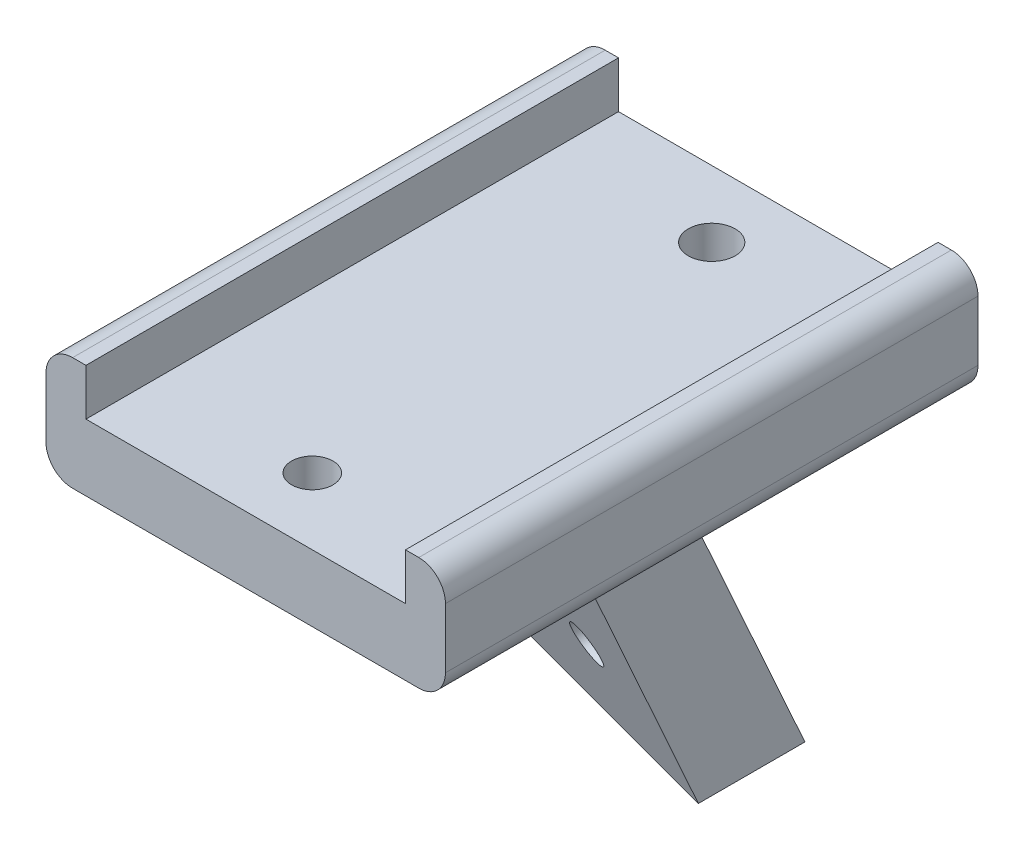
SolidWorks part; units mm, degrees
ref_plane "Front Plane" through (0, 0, 0) normal (0, 0, 1) x (1, 0, 0)
ref_plane "Top Plane" through (0, 0, 0) normal (0, 1, 0) x (1, 0, 0)
ref_plane "Right Plane" through (0, 0, 0) normal (1, 0, 0) x (0, 0, -1)
sketch "Sketch1" plane through (0, 0, 0) normal (0, 1, 0) x (1, 0, 0)
  line L1 (-11, -20) -> (11, -20)
  line L2 (-11, -20) -> (-11, 20)
  line L3 (-11, 20) -> (11, 20)
  line L4 (11, -20) -> (11, 20)
  line L5 (-11, -20) -> (11, 20) construction
  line L6 (-11, 20) -> (11, -20) construction
  circle A0 centre (0, 15) radius 1.7606
  circle A1 centre (0, -15) radius 1.5554
  point P0 (0, 0)
  dimension "D3" = 30
  dimension "D4" = 15
  dimension "D1" = 22
  dimension "D2" = 40
extrude "Boss-Extrude1" add sketch "Sketch1" along normal blind 5
sketch "Sketch2" plane through (0, 0, 0) normal (0, -1, 0) x (1, 0, 0)
  line L0 (-11, 0.1051) -> (11, 6)
  line L1 (-11, -20) -> (-11, 20) construction
  line L2 (11, 20) -> (11, -20) construction
  line L3 (11, 6) -> (11, -2)
  line L4 (11, -2) -> (-11, -7.8949)
  line L5 (-11, -7.8949) -> (-11, 0.1051)
  dimension "D1" = 8
  dimension "D2" = 14
  dimension "D3" = 105
sketch "Sketch4" plane through (0, 0, -20) normal (0, 0, -1) x (-1, 0, 0)
  line L0 (-11, 5) -> (-12, 5)
  line L1 (-12, 5) -> (-12, 8.5)
  line L2 (-12, 8.5) -> (-15, 8.5)
  line L3 (-15, 8.5) -> (-15, 0)
  line L4 (-15, 0) -> (-11, 0)
  line L5 (-11, 0) -> (-11, 5)
  line L6 (0, 0) -> (0, 5) construction
  line L7 (-11, 0) -> (11, 0) construction
  line L8 (-11, 5) -> (11, 5) construction
  line L9 (11, 0) -> (11, 5)
  line L10 (15, 0) -> (11, 0)
  line L11 (15, 8.5) -> (15, 0)
  line L12 (12, 8.5) -> (15, 8.5)
  line L13 (12, 5) -> (12, 8.5)
  line L14 (11, 5) -> (12, 5)
  dimension "D1" = 1
  dimension "D2" = 3.5
  dimension "D3" = 3
extrude "Boss-Extrude3" add sketch "Sketch4" against normal up to surface (40 mm away) up to face at (0, 2.5, 20)
fillet "Fillet1" radius 2 4 edges at (15, 0, 0) (-15, 0, 0) (-15, 8.5, 0) (15, 8.5, 0)
ref_plane "Plane1" through (0, -20, 0) normal (0, -1, 0) x (-1, 0, 0)
sketch "Sketch5" plane through (0, -20, 0) normal (0, -1, 0) x (-1, 0, 0)
  line L0 (-11, 3) -> (-11, 11)
  line L1 (-11, 11) -> (11, 16.8949)
  line L2 (11, 16.8949) -> (11, 8.8949)
  line L3 (11, 8.8949) -> (-11, 3)
  line L4 (-13, 20) -> (-13, -20) construction
  line L5 (13, -20) -> (13, 20) construction
  line L6 (13, -20) -> (-13, -20) construction
  dimension "D1" = 8
  dimension "D2" = 2
  dimension "D3" = 2
  dimension "D4" = 105
  dimension "D5" = 23
loft "Loft1" add profiles "Sketch2", "Sketch5"
ref_plane "Plane2" through (1.0403, 1.7471, -3.8825) normal (-0.2374, -0.3986, 0.8859) x (0.9714, -0.0974, 0.2165)
sketch "Sketch6" plane through (1.0403, 1.7471, -3.8825) normal (-0.2374, -0.3986, 0.8859) x (0.9714, -0.0974, 0.2165)
  line L0 (10.2527, -0.8207) -> (10.2527, -22.7524) construction
  line L1 (-12.3945, -3.2398) -> (-12.3945, -25.1715) construction
  line L2 (-12.3945, -3.2398) -> (10.2527, -0.8207) construction
  circle A0 centre (5.2527, -11.4117) radius 1.5
  circle A1 centre (-7.3945, -12.7626) radius 1.5
  point P6 (10.2527, -11.7866)
  dimension "D1" = 3
  dimension "D2" = 3
  dimension "D3" = 5
  dimension "D4" = 5
  dimension "D5" = 10
  dimension "D6" = 10
extrude "Cut-Extrude1" cut sketch "Sketch6" along normal up to surface (7.0869 mm away) up to face at (5.5, -5, 2.2763)
